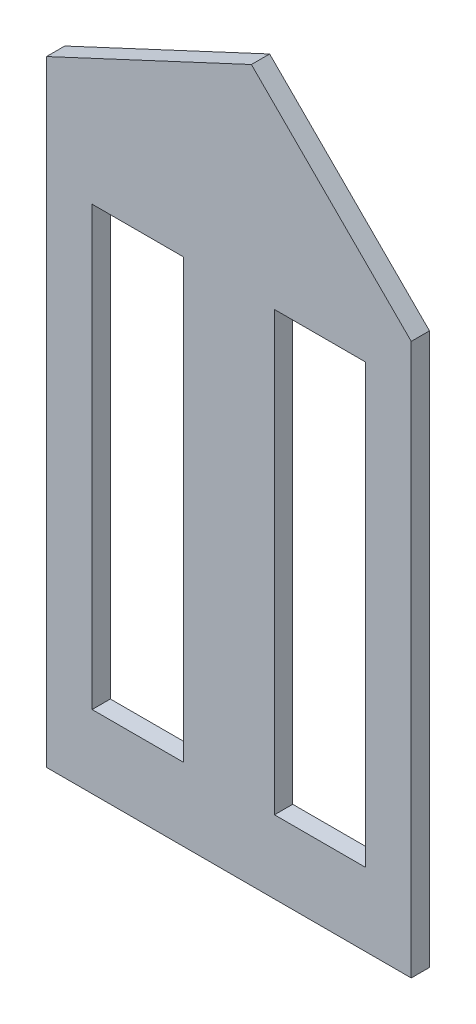
SolidWorks part; units mm, degrees
material "Beech"
ref_plane "Front Plane" through (0, 0, 0) normal (0, 0, 1) x (1, 0, 0)
ref_plane "Top Plane" through (0, 0, 0) normal (0, 1, 0) x (1, 0, 0)
ref_plane "Right Plane" through (0, 0, 0) normal (1, 0, 0) x (0, 0, -1)
sketch "Sketch1" plane through (0, 0, 0) normal (0, 0, 1) x (1, 0, 0)
  line L1 (0, 0) -> (127, 0)
  line L2 (0, 0) -> (0, 247.65)
  line L3 (0, 247.65) -> (127, 247.65)
  line L4 (127, 0) -> (127, 247.65)
  dimension "D1" = 127
  dimension "D2" = 247.65
extrude "Boss-Extrude1" add sketch "Sketch1" along normal blind 6.35
sketch "Sketch2" plane through (0, 0, 6.35) normal (0, 0, 1) x (1, 0, 0)
  line L0 (71.3397, 247.65) -> (0, 214.3838)
  line L1 (127, 247.65) -> (0, 247.65) construction
  line L2 (0, 247.65) -> (0, 0) construction
  line L3 (0, 214.3838) -> (0, 247.65)
  line L4 (0, 247.65) -> (71.3397, 247.65)
  line L5 (71.3397, 247.65) -> (127, 191.9897)
  line L6 (127, 0) -> (127, 247.65) construction
  line L7 (127, 191.9897) -> (127, 247.65)
  line L8 (127, 247.65) -> (71.3397, 247.65)
  line M5 (0, 247.65) -> (0, 0)
  line M7 (127, 0) -> (127, 247.65)
  line M8 (127, 247.65) -> (0, 247.65)
  dimension "D1" = 78.7146
  dimension "D2" = 25
  dimension "D3" = 45
extrude "Cut-Extrude1" cut sketch "Sketch2" against normal through all contours L0 M8 M5 | L5 M8 M7
sketch "Sketch3" plane through (0, 0, 6.35) normal (0, 0, 1) x (1, 0, 0)
  line L0 (0, 0) -> (127, 0) construction
  line L1 (15.875, 177.8) -> (47.625, 177.8)
  line L2 (15.875, 177.8) -> (15.875, 25.4)
  line L3 (15.875, 25.4) -> (47.625, 25.4)
  line L4 (47.625, 177.8) -> (47.625, 25.4)
  line L5 (79.375, 177.8) -> (111.125, 177.8)
  line L6 (79.375, 177.8) -> (79.375, 25.4)
  line L7 (79.375, 25.4) -> (111.125, 25.4)
  line L8 (111.125, 177.8) -> (111.125, 25.4)
  line L9 (127, 0) -> (127, 191.9897) construction
  line L10 (0, 214.3838) -> (0, 0) construction
  dimension "D1" = 31.75
  dimension "D2" = 152.4
  dimension "D3" = 25.4
  dimension "D4" = 15.875
  dimension "D5" = 15.875
extrude "Cut-Extrude2" cut sketch "Sketch3" against normal through all
ref_plane "Plane1" through (63.5, 0, 0) normal (1, 0, 0) x (0, 0, -1)
